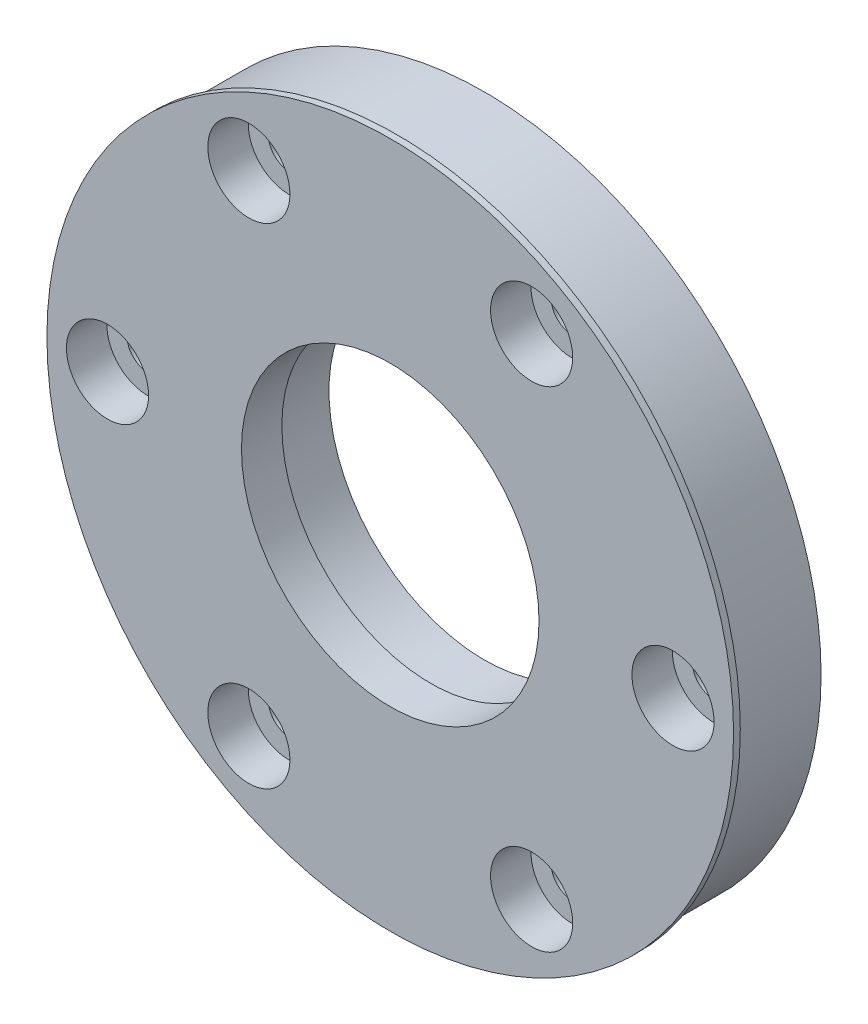
SolidWorks part; units mm, degrees
material "ABS"
ref_plane "Front Plane" through (0, 0, 0) normal (0, 0, 1) x (1, 0, 0)
ref_plane "Top Plane" through (0, 0, 0) normal (0, 1, 0) x (1, 0, 0)
ref_plane "Right Plane" through (0, 0, 0) normal (1, 0, 0) x (0, 0, -1)
sketch "Output Master Sketch" plane through (0, 0, 0) normal (0, 0, 1) x (1, 0, 0)
  circle A0 centre (0, 0) radius 21 construction
  circle A1 centre (21, 0) radius 3.05 construction
  circle A2 centre (10.5, -18.1865) radius 3.05 construction
  circle A3 centre (-10.5, -18.1865) radius 3.05 construction
  circle A4 centre (-21, 0) radius 3.05 construction
  circle A5 centre (-10.5, 18.1865) radius 3.05 construction
  circle A6 centre (10.5, 18.1865) radius 3.05 construction
  circle A7 centre (0, 0) radius 25
  point P17 (0, 0)
sketch "Sketch2" plane through (0, 0, 0) normal (0, 0, 1) x (1, 0, 0)
  circle A0 centre (0, 0) radius 25
  circle A1 centre (0, 0) radius 25 construction
extrude "Boss-Extrude1" add sketch "Sketch2" along normal blind 7
sketch "Sketch3" plane through (0, 0, 7) normal (0, 0, 1) x (1, 0, 0)
  circle A0 centre (-21, 0) radius 3.05
  circle A1 centre (-21, 0) radius 3.05 construction
  circle A2 centre (-10.5, 18.1865) radius 3.05
  circle A3 centre (10.5, 18.1865) radius 3.05
  circle A4 centre (21, 0) radius 3.05
  circle A5 centre (10.5, -18.1865) radius 3.05
  circle A6 centre (-10.5, -18.1865) radius 3.05
  point P18 (0, 0)
  dimension "D1" = 6.1
  dimension "D2" = 6
extrude "Dowel Pin Cutout" cut sketch "Sketch3" against normal blind 3
sketch "Sketch4" plane through (0, 0, 7) normal (0, 0, 1) x (1, 0, 0)
  circle A0 centre (0, 0) radius 25
  circle A1 centre (0, 0) radius 25.5
  circle A3 centre (0, 0) radius 25 construction
  dimension "D1" = 0.5
extrude "Main Housing Bearing Retainer" add sketch "Sketch4" against normal blind 0.5
sketch "Sketch5" plane through (0, 0, 0) normal (0, 0, -1) x (-1, 0, 0)
  circle A0 centre (-21, 0) radius 1.55
  circle A1 centre (-10.5, 18.1865) radius 1.55
  circle A2 centre (10.5, 18.1865) radius 1.55
  circle A3 centre (21, 0) radius 1.55
  circle A4 centre (10.5, -18.1865) radius 1.55
  circle A5 centre (-10.5, -18.1865) radius 1.55
  point P15 (0, 0)
  dimension "D1" = 3.1
  dimension "D2" = 6
extrude "M3 Thru" cut sketch "Sketch5" against normal through all
sketch "Sketch6" plane through (0, 0, 0) normal (0, 0, -1) x (-1, 0, 0)
  circle A0 centre (-21, 0) radius 3
  circle A1 centre (-10.5, 18.1865) radius 3
  circle A2 centre (10.5, 18.1865) radius 3
  circle A3 centre (21, 0) radius 3
  circle A4 centre (10.5, -18.1865) radius 3
  circle A5 centre (-10.5, -18.1865) radius 3
  point P15 (0, 0)
  dimension "D1" = 6
  dimension "D2" = 6
extrude "M3 Button Head Cutout" cut sketch "Sketch6" against normal blind 1.7
sketch "Sketch8" plane through (0, 0, 7) normal (0, 0, 1) x (1, 0, 0)
  circle A0 centre (0, 0) radius 11.55
  dimension "D1" = 23.1
extrude "Input Shaft Bearing Cutout" cut sketch "Sketch8" against normal through all
sketch "Sketch9" plane through (0, 0, 0) normal (0, 0, -1) x (-1, 0, 0)
  circle A0 centre (0, 0) radius 11.55
  circle A1 centre (0, 0) radius 11.05
  circle A2 centre (0, 0) radius 11.55 construction
  dimension "D1" = 0.5
extrude "Input Shaft Bearing Retainer" add sketch "Sketch9" along normal blind 3 from surface at -7 starting at face at (11.55, 0, 7)
